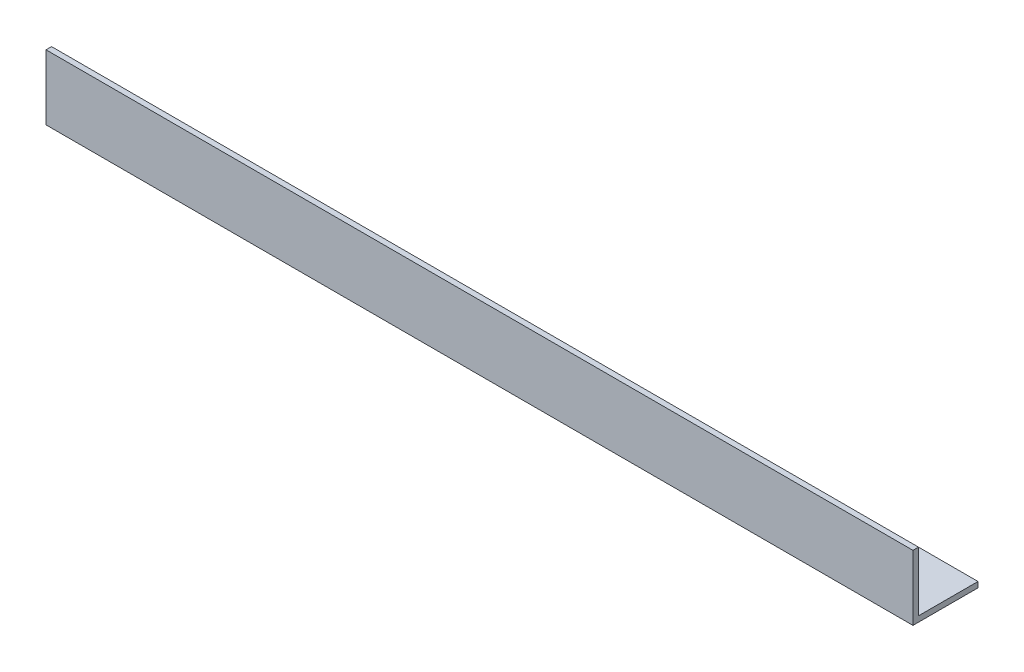
SolidWorks part; units mm, degrees
ref_plane "Front Plane" through (0, 0, 0) normal (0, 0, 1) x (1, 0, 0)
ref_plane "Top Plane" through (0, 0, 0) normal (0, 1, 0) x (1, 0, 0)
ref_plane "Right Plane" through (0, 0, 0) normal (1, 0, 0) x (0, 0, -1)
sketch "Sketch1" plane through (0, 0, 0) normal (1, 0, 0) x (0, 0, -1)
  line L0 (-7.8994, -7.8994) -> (9.525, -7.8994)
  line L1 (-9.525, -9.525) -> (9.525, -9.525)
  line L2 (-9.525, -9.525) -> (-9.525, 9.525)
  line L3 (-7.8994, -7.8994) -> (-7.8994, 9.525)
  line L4 (9.525, -9.525) -> (9.525, -7.8994)
  line L5 (-9.525, 9.525) -> (-7.8994, 9.525)
  dimension "D1" = 19.05
  dimension "D2" = 1.6256
extrude "Boss-Extrude1" add sketch "Sketch1" along normal blind 254
